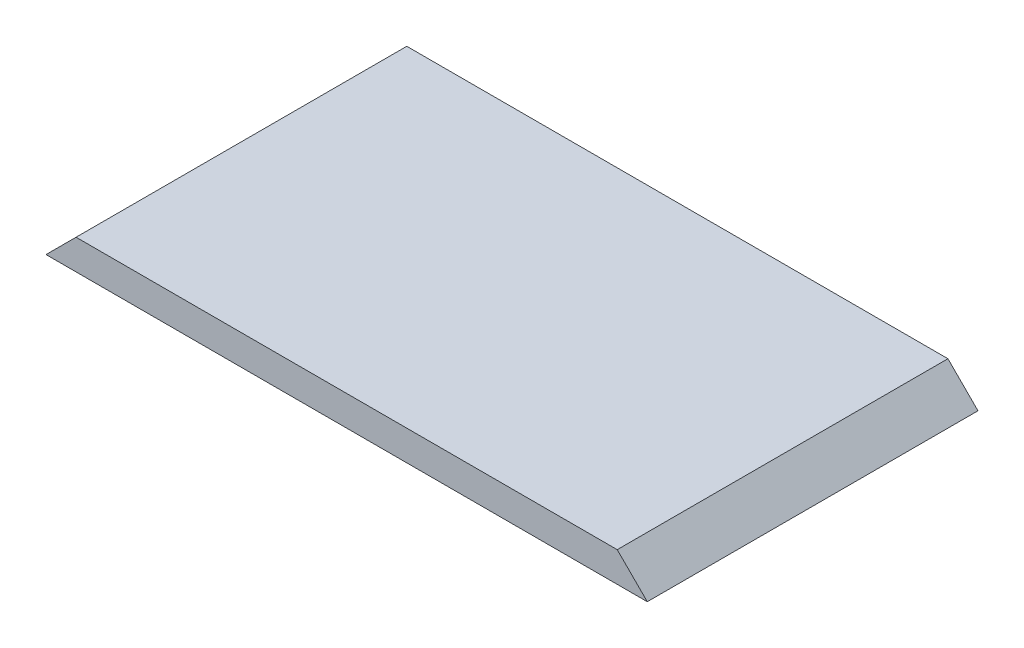
SolidWorks part; units mm, degrees
ref_plane "Front Plane" through (0, 0, 0) normal (0, 0, 1) x (1, 0, 0)
ref_plane "Top Plane" through (0, 0, 0) normal (0, 1, 0) x (1, 0, 0)
ref_plane "Right Plane" through (0, 0, 0) normal (1, 0, 0) x (0, 0, -1)
sketch "Sketch2" plane through (0, 0, 0) normal (0, 1, 0) x (1, 0, 0)
  line L1 (0, 0) -> (-100, 0)
  line L2 (0, 0) -> (0, 55)
  line L3 (0, 55) -> (-100, 55)
  line L4 (-100, 0) -> (-100, 55)
  dimension "D1" = 55
  dimension "D2" = 100
extrude "Boss-Extrude1" add sketch "Sketch2" along normal blind 5
sketch "Sketch3" plane through (0, 0, 0) normal (0, 0, 1) x (1, 0, 0)
  line L0 (-100, 0) -> (-95, 5)
  line L2 (-100, 5) -> (0, 5) construction
  line L3 (-100, 5) -> (-100, 0)
  line L4 (-95, 5) -> (-100, 5)
sketch "Sketch5" plane through (0, 0, 0) normal (0, 0, 1) x (1, 0, 0)
  line L0 (0, 0) -> (-5, 5)
  line L1 (-100, 5) -> (0, 5) construction
  line L2 (-5, 5) -> (0, 5)
  line L3 (0, 5) -> (0, 0)
extrude "Cut-Extrude2" cut sketch "Sketch5" against normal up to next
extrude "Cut-Extrude3" cut sketch "Sketch3" against normal blind 66
